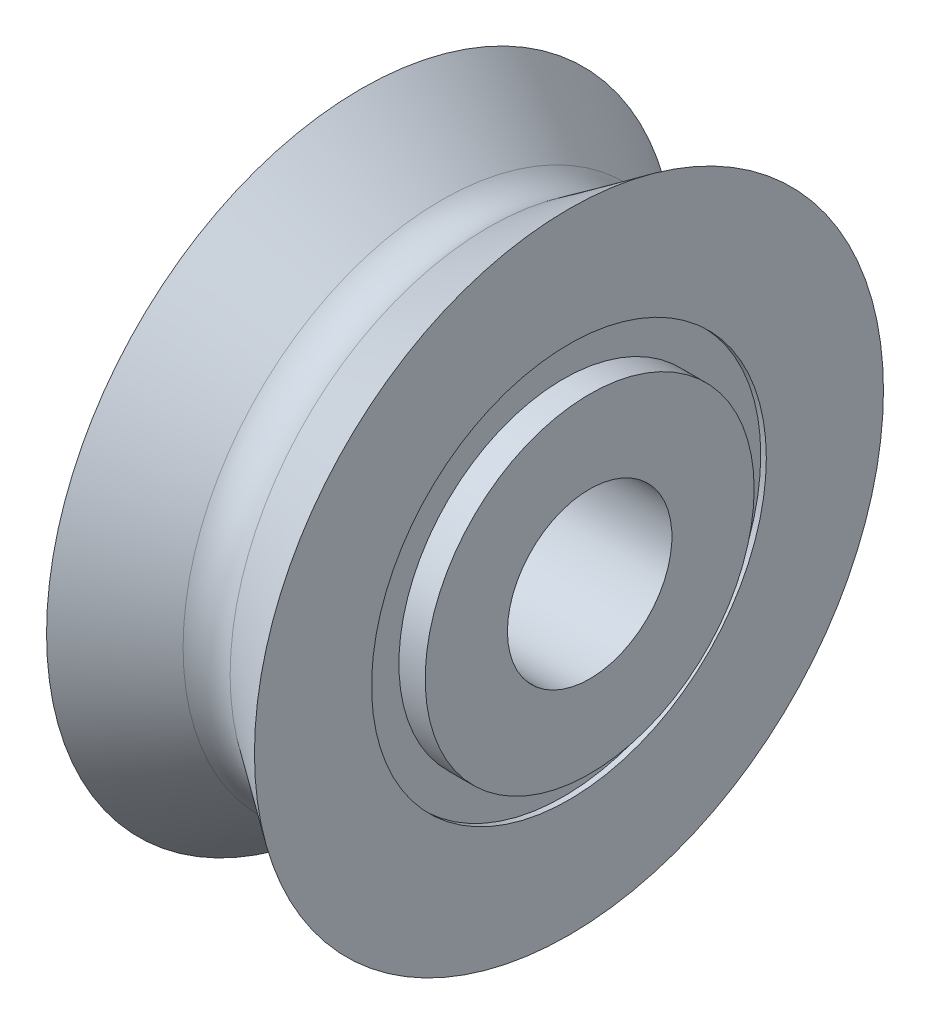
SolidWorks part; units mm, degrees
material "Plain Carbon Steel"
ref_plane "Front Plane" through (0, 0, 0) normal (0, 0, 1) x (1, 0, 0)
ref_plane "Top Plane" through (0, 0, 0) normal (0, 1, 0) x (1, 0, 0)
ref_plane "Right Plane" through (0, 0, 0) normal (1, 0, 0) x (0, 0, -1)
sketch "Sketch1" plane through (0, 0, 0) normal (0, 0, 1) x (1, 0, 0)
  line L0 (0, 0) -> (4.8133, 0) construction
  line L1 (0, 1.5875) -> (4.8133, 1.5875)
  line L2 (4.8133, 1.5875) -> (4.8133, 6.35)
  line L3 (4.8133, 6.35) -> (2.8608, 4.9878)
  line L4 (1.9525, 4.9878) -> (0, 6.35)
  line L5 (0, 6.35) -> (0, 1.5875)
  line L6 (0, 1.5875) -> (0, 0) construction
  line L7 (4.8133, 1.5875) -> (4.8133, 0) construction
  line L8 (0, 4.845) -> (4.8133, 4.845) construction
  arc A0 (2.8608, 4.9878) -> (1.9525, 4.9878) centre (2.4067, 5.6388) cw
  dimension "D1" = 0.7937
  dimension "D3" = 12.7
  dimension "D2" = 3.175
  dimension "D5" = 4.845
  dimension "D6" = 4.8133
revolve "Revolve1" add sketch "Sketch1" angle 360 about L0
sketch "Sketch4" plane through (4.8133, 0, 0) normal (1, 0, 0) x (0, 0, -1)
  line L0 (0, 1.5875) -> (0, 3.175) construction
  line L1 (0, 3.175) -> (0, 3.81) construction
  line L2 (0, 3.81) -> (0, 6.35) construction
  line L3 (0, 1.5875) -> (0, 0) construction
  circle A0 centre (0, 0) radius 3.175
  circle A1 centre (0, 0) radius 3.81
  circle A2 centre (0, 0) radius 1.5875 construction
  circle A4 centre (0, 0) radius 6.35 construction
  dimension "D1" = 6.35
  dimension "D2" = 0.635
extrude "Cut-Extrude1" cut sketch "Sketch4" against normal blind 0.508
sketch "Sketch5" plane through (0, 0, 0) normal (-1, 0, 0) x (0, 0, 1)
  line L0 (0, 2.3813) -> (0, 3.175) construction
  line L1 (0, 3.175) -> (0, 3.81) construction
  line L2 (0, 3.81) -> (0, 6.35) construction
  line L3 (0, 2.3813) -> (0, 0) construction
  circle A0 centre (0, 0) radius 3.175
  circle A1 centre (0, 0) radius 3.81
  circle A4 centre (0, 0) radius 3.175 construction
  circle A5 centre (0, 0) radius 3.81 construction
extrude "Cut-Extrude2" cut sketch "Sketch5" against normal blind 0.508
sketch "Sketch7" plane through (4.8133, 0, 0) normal (1, 0, 0) x (0, 0, -1)
  circle A0 centre (0, 0) radius 3.81 construction
  circle A1 centre (0, 0) radius 6.35
  circle A2 centre (0, 0) radius 6.35
  circle A3 centre (0, 0) radius 3.81
  dimension "D1" = 0
extrude "Cut-Extrude3" cut sketch "Sketch7" against normal blind 0.4001
sketch "Sketch8" plane through (0, 0, 0) normal (-1, 0, 0) x (0, 0, 1)
  circle A0 centre (0, 0) radius 3.81 construction
  circle A1 centre (0, 0) radius 6.35
  circle A2 centre (0, 0) radius 6.35
  circle A3 centre (0, 0) radius 3.81
  dimension "D1" = 0
extrude "Cut-Extrude4" cut sketch "Sketch8" against normal blind 0.4001
